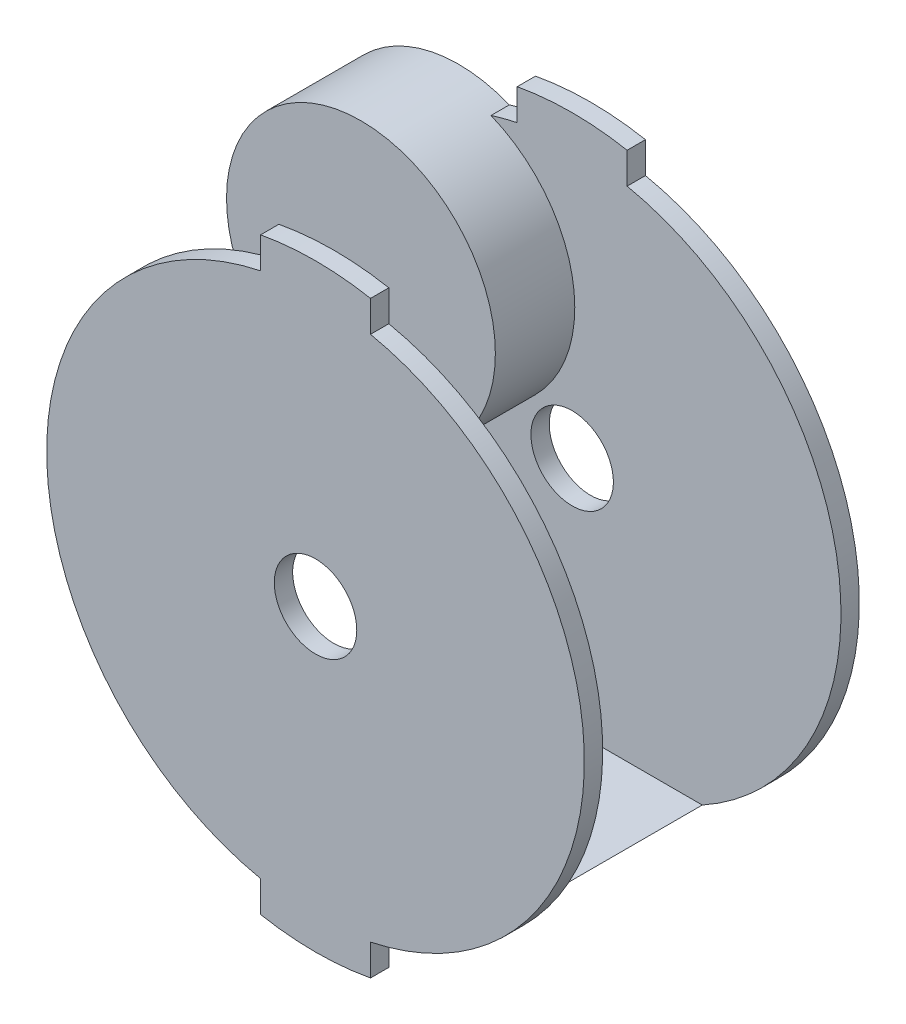
SolidWorks part; units mm, degrees
ref_plane "Front Plane" through (0, 0, 0) normal (0, 0, 1) x (1, 0, 0)
ref_plane "Top Plane" through (0, 0, 0) normal (0, 1, 0) x (1, 0, 0)
ref_plane "Right Plane" through (0, 0, 0) normal (1, 0, 0) x (0, 0, -1)
sketch "Sketch1" plane through (0, 0, 0) normal (0, 0, 1) x (1, 0, 0)
  line L0 (-2.286, 12.2343) -> (-2.286, 10.9397)
  line L1 (2.286, 12.2343) -> (2.286, 10.9397)
  line L2 (2.286, 12.2343) -> (-2.286, -12.2343) construction
  line L3 (-2.286, -10.9397) -> (-2.286, -12.2343)
  line L4 (2.286, -10.9397) -> (2.286, -12.2343)
  arc A0 (2.286, -10.9397) -> (2.286, 10.9397) centre (0, 0) ccw
  circle A1 centre (0, 0) radius 1.7145
  arc A2 (-2.286, -12.2343) -> (2.286, -12.2343) centre (0, 0) ccw
  arc A3 (2.286, 12.2343) -> (-2.286, 12.2343) centre (0, 0) ccw
  arc A4 (-2.286, 10.9397) -> (-2.286, -10.9397) centre (0, 0) ccw
  dimension "D1" = 22.352
  dimension "D2" = 3.429
  dimension "D3" = 4.572
  dimension "D4" = 24.892
extrude "Boss-Extrude1" add sketch "Sketch1" along normal blind 11.43
sketch "Sketch2" plane through (0, 0, 0) normal (1, 0, 0) x (0, 0, -1)
  line L0 (-11.43, 1.7145) -> (-11.43, -1.7145) construction
  line L1 (-10.668, 11.176) -> (-0.762, 11.176)
  line L2 (-10.668, 11.176) -> (-10.668, 13.716)
  line L3 (-10.668, 13.716) -> (-0.762, 13.716)
  line L4 (-0.762, 11.176) -> (-0.762, 13.716)
  line L5 (-10.668, 11.176) -> (-0.762, 13.716) construction
  line L6 (-10.668, 13.716) -> (-0.762, 11.176) construction
  point P0 (-5.715, 12.446)
  dimension "D1" = 11.176
  dimension "D2" = 0.762
  dimension "D3" = 0.762
  dimension "D4" = 2.54
ref_axis "Axis1" through (0, 0, 11.43) along (0, 0, -1)
revolve "Cut-Revolve1" cut sketch "Sketch2" angle 360 about axis through (0, 0, 11.43) along (0, 0, -1)
sketch "Sketch4" plane through (0, 0, 0) normal (1, 0, 0) x (0, 0, -1)
  line L0 (-0.762, 11.176) -> (-10.668, 11.176) construction
  line L1 (-0.762, 11.176) -> (-10.668, 11.176)
  line L2 (-0.762, 11.176) -> (-0.762, -9.779)
  line L3 (-0.762, -9.779) -> (-10.668, -9.779)
  line L4 (-10.668, 11.176) -> (-10.668, -9.779)
  line L6 (-10.668, 10.9397) -> (-10.668, 11.176) construction
  line L7 (-0.762, 11.176) -> (-0.762, 10.9397) construction
  line L8 (-0.762, -10.9397) -> (-0.762, -11.176) construction
  line L9 (-0.762, -11.176) -> (-10.668, -11.176)
  line L10 (-0.762, -11.176) -> (-0.762, -10.541)
  line L11 (-0.762, -10.541) -> (-10.668, -10.541)
  line L12 (-10.668, -11.176) -> (-10.668, -10.541)
  dimension "D1" = 20.955
  dimension "D2" = 0.635
extrude "Cut-Extrude1" cut sketch "Sketch4" against normal through all and the other way through all
sketch "Sketch3" plane through (0, 0, 0) normal (0, 0, 1) x (1, 0, 0)
  line L0 (0, 0) -> (-9.4293, 9.4293) construction
  line L1 (0, 0) -> (-17.0892, 0) construction
  circle A0 centre (-5.478, 5.478) radius 5.588
  dimension "D1" = 11.176
  dimension "D2" = 13.335
  dimension "D3" = 17.0892
  dimension "D4" = 45
extrude "Boss-Extrude2" add sketch "Sketch3" along normal blind 4.064
